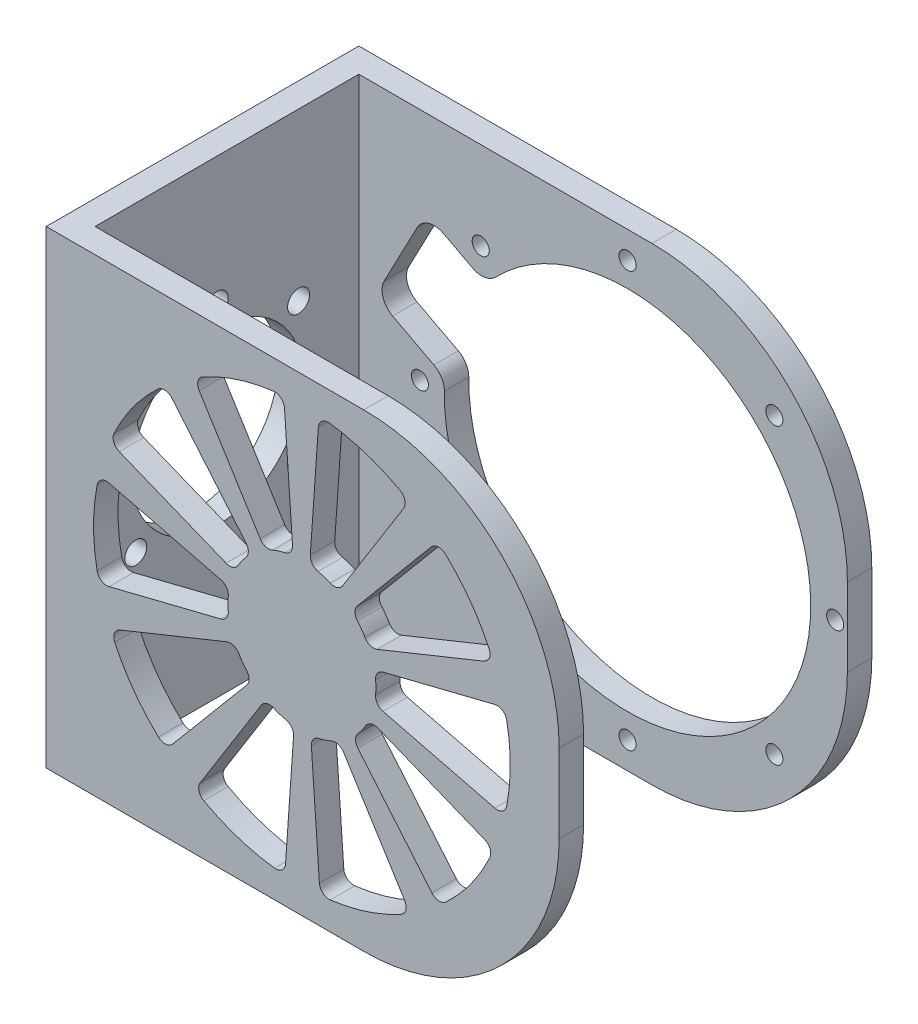
SolidWorks part; units mm, degrees
material "6061 合金"
ref_plane "前视基准面" through (0, 0, 0) normal (0, 0, 1) x (1, 0, 0)
ref_plane "上视基准面" through (0, 0, 0) normal (0, 1, 0) x (1, 0, 0)
ref_plane "右视基准面" through (0, 0, 0) normal (1, 0, 0) x (0, 0, -1)
other "Configuration Table"
sketch "草图1" plane through (0, 0, 0) normal (1, 0, 0) x (0, 0, -1)
  line L0 (-83.5786, 0) -> (71.0535, 0) construction
  line L1 (0, 49.275) -> (0, -51.1598) construction
  line L3 (-32, 48) -> (32, 48)
  line L4 (-32, 48) -> (-32, -48)
  line L5 (-32, -48) -> (32, -48)
  line L6 (32, 48) -> (32, -48)
  dimension "D1" = 64
  dimension "D2" = 96
extrude "凸台-拉伸1" add sketch "草图1" along normal blind 5
sketch "草图3" plane through (5, 0, 0) normal (1, 0, 0) x (0, 0, -1)
  line L0 (32, 48) -> (-32, 48) construction
  line L1 (27, 48) -> (32, 48)
  line L2 (27, 48) -> (27, -48)
  line L3 (27, -48) -> (32, -48)
  line L4 (32, 48) -> (32, -48)
  line L5 (0, 33.3664) -> (0, -30.3664) construction
  line L6 (-27, -48) -> (-32, -48)
  line L7 (-32, 48) -> (-32, -48)
  line L8 (-27, 48) -> (-32, 48)
  line L9 (-27, 48) -> (-27, -48)
  dimension "D1" = 5
extrude "凸台-拉伸2" add sketch "草图3" along normal blind 100 contours L2 L1 L4 L3
sketch "草图4" plane through (0, 0, 0) normal (-1, 0, 0) x (0, 0, 1)
  line L0 (-42.5996, 0) -> (43.5329, 0) construction
  line L1 (2, 63.7809) -> (2, -33.233) construction
  line L2 (32, 48) -> (32, -48) construction
  line L3 (2, 0) -> (18.6615, 13.9806) construction
  circle A0 centre (2, 0) radius 46 construction
  circle A1 centre (2, 0) radius 21.75 construction
  circle A2 centre (2, 21.75) radius 2.25
  circle A15 centre (18.6615, 13.9806) radius 2.25
  circle A16 centre (-14.6615, 13.9806) radius 2.25
  circle A17 centre (2, -21.75) radius 2.25
  circle A18 centre (18.6615, -13.9806) radius 2.25
  circle A19 centre (-14.6615, -13.9806) radius 2.25
  circle A20 centre (2, 0) radius 17.5
  point P24 (2, 0)
  point P28 (2, 0)
  dimension "D2" = 92
  dimension "D3" = 43.5
  dimension "D4" = 4.5
  dimension "D6" = 35
  dimension "D1" = 30
  dimension "D5" = 50
extrude "切除-拉伸1" cut sketch "草图4" against normal blind 100
sketch "草图5" plane through (0, 0, -32) normal (0, 0, -1) x (-1, 0, 0)
  line L0 (0, 0) -> (-122.5794, 0) construction
  line L1 (0, -48) -> (0, 48) construction
  circle A0 centre (-60, 0) radius 42.5 construction
  circle A1 centre (-60, 42.5) radius 1.75
  circle A2 centre (-29.948, 30.052) radius 1.75
  circle A3 centre (-17.5, 0) radius 1.75
  circle A4 centre (-29.948, -30.052) radius 1.75
  circle A5 centre (-60, -42.5) radius 1.75
  circle A6 centre (-90.052, -30.052) radius 1.75
  circle A7 centre (-102.5, 0) radius 1.75
  circle A8 centre (-90.052, 30.052) radius 1.75
  circle A9 centre (-60, 0) radius 37.5
  point P25 (-60, 0)
  dimension "D1" = 85
  dimension "D3" = 3.5
  dimension "D5" = 75
  dimension "D2" = 60
  dimension "D4" = 8
extrude "切除-拉伸2" cut sketch "草图5" against normal blind 22
fillet "圆角1" radius 40 4 edges at (105, -48, -29.5) (105, 48, -29.5) (2.5, 48, 32) (2.5, -48, 32)
sketch "草图6" plane through (0, 0, -27) normal (0, 0, 1) x (1, 0, 0)
  line L0 (10.2147, 13.9946) -> (16.9094, 26.7361)
  line L1 (22.3109, 28.4166) -> (38.876, 19.7129)
  line L2 (38.876, 19.7129) -> (28.4603, -0.1106)
  line L3 (28.4603, -0.1106) -> (11.8951, 8.5931)
  circle A0 centre (29.948, 30.052) radius 1.75 construction
  circle A1 centre (17.5, 0) radius 1.75 construction
  arc A2 (10.2147, 13.9946) -> (11.8951, 8.5931) centre (13.7556, 12.1341) ccw
  arc A3 (16.9094, 26.7361) -> (22.3109, 28.4166) centre (20.4503, 24.8756) cw
  dimension "D4" = 4
  dimension "D1" = 5
  dimension "D2" = 5
  dimension "D3" = 10
extrude "切除-拉伸3" cut sketch "草图6" against normal blind 10
fillet "圆角2" radius 4 2 edges at (22.617, 2.9596, -29.5) (31.0437, 23.8282, -29.5)
sketch "草图7" plane through (5, 0, 0) normal (1, 0, 0) x (0, 0, -1)
  line L1 (-27, 48) -> (8, 48)
  line L3 (-27, -48) -> (8, -48)
  line L5 (-27, 48) -> (0, 0) construction
  line L6 (-27, -48) -> (0, 0) construction
  line L7 (-27, 48) -> (-32, 48)
  line L9 (-27, -48) -> (-32, -48)
  line L10 (-32, 48) -> (-32, -48)
  arc A0 (-32, -8) -> (8, -48) centre (8, -8) ccw construction
  arc A1 (8, 48) -> (-32, 8) centre (8, 8) ccw construction
  arc A2 (-32, -8) -> (8, -48) centre (8, -8) ccw
  arc A3 (8, 48) -> (-32, 8) centre (8, 8) ccw
  point P0 (0, 0)
  arc M11 (8, 48) -> (-32, 8) centre (8, 8) ccw
  arc M13 (-32, -8) -> (8, -48) centre (8, -8) ccw
extrude "凸台-拉伸3" add sketch "草图7" against normal blind 5 contours L7 L10 L1 M11 | L10 L9 L3 M13
sketch "草图8" plane through (0, 0, 32) normal (0, 0, 1) x (1, 0, 0)
  line L4 (5, -48) -> (65, -48)
  line L5 (105, -8) -> (105, 8)
  line L6 (65, 48) -> (5, 48)
  line L7 (5, 48) -> (5, -48)
  line L8 (5, -48) -> (65, -48)
  line L9 (105, -8) -> (105, 8)
  line L10 (65, 48) -> (5, 48)
  line L11 (5, 48) -> (5, -48)
  arc A2 (65, -48) -> (105, -8) centre (65, -8) ccw
  arc A3 (105, 8) -> (65, 48) centre (65, 8) ccw
  arc A4 (65, -48) -> (105, -8) centre (65, -8) ccw
  arc A5 (105, 8) -> (65, 48) centre (65, 8) ccw
  dimension "D1" = 0
extrude "凸台-拉伸4" add sketch "草图8" against normal blind 5
sketch "草图9" plane through (0, 0, 32) normal (0, 0, 1) x (1, 0, 0)
  line L0 (0, 48) -> (0, -48) construction
  line L1 (0, 48) -> (65, 48) construction
  line L2 (68.9348, 3.4743) -> (91.8201, 9.1803)
  line L3 (68.9348, -3.4743) -> (91.8201, -9.1803)
  line L4 (55, 0) -> (95, 0) construction
  line L5 (67.8754, -6.9601) -> (89.7439, -15.7955)
  line L6 (63.791, -12.5817) -> (78.9518, -30.6496)
  line L7 (54.5597, -1.5802) -> (86.9204, -25.0916) construction
  line L8 (60.885, -14.779) -> (73.3837, -34.781)
  line L9 (54.2765, -16.9263) -> (55.9217, -40.4548)
  line L10 (53.2747, -2.5999) -> (65.6353, -40.6421) construction
  line L11 (50.6339, -16.9958) -> (48.9886, -40.5243)
  line L12 (44.0253, -14.8486) -> (31.5267, -34.8506)
  line L13 (51.6357, -2.6694) -> (39.275, -40.7117) construction
  line L14 (41.0376, -12.7638) -> (25.8768, -30.8317)
  line L15 (36.9532, -7.1422) -> (15.0847, -15.9777)
  line L16 (50.2689, -1.7624) -> (17.9082, -25.2738) construction
  line L17 (35.7615, -3.6995) -> (12.8761, -9.4054)
  line L18 (35.7615, 3.2492) -> (12.8761, 8.9552)
  line L19 (49.6963, -0.2251) -> (9.6963, -0.2251) construction
  line L20 (36.8209, 6.735) -> (14.9524, 15.5704)
  line L21 (40.9052, 12.3566) -> (25.7445, 30.4244)
  line L22 (50.1366, 1.3551) -> (17.7759, 24.8665) construction
  line L23 (43.8112, 14.5539) -> (31.3126, 34.5559)
  line L24 (50.4198, 16.7011) -> (48.7745, 40.2296)
  line L25 (51.4216, 2.3747) -> (39.0609, 40.417) construction
  line L26 (54.0623, 16.7707) -> (55.7076, 40.2992)
  line L27 (60.6709, 14.6235) -> (73.1696, 34.6255)
  line L28 (53.0605, 2.4443) -> (65.4212, 40.4866) construction
  line L29 (63.6587, 12.5387) -> (78.8194, 30.6066)
  line L30 (67.743, 6.9171) -> (89.6115, 15.7526)
  line L31 (54.4274, 1.5372) -> (86.7881, 25.0486) construction
  arc A0 (94.2673, -7.6207) -> (94.2673, 7.6207) centre (55, 0) ccw
  arc A1 (67.4299, -1.3222) -> (67.4299, 1.3222) centre (55, 0) ccw
  arc A2 (91.8201, -9.1803) -> (94.2673, -7.6207) centre (92.304, -7.2397) ccw
  arc A3 (91.8201, 9.1803) -> (94.2673, 7.6207) centre (92.304, 7.2397) cw
  arc A4 (67.4299, -1.3222) -> (68.9348, -3.4743) centre (69.4187, -1.5337) ccw
  arc A5 (67.4299, 1.3222) -> (68.9348, 3.4743) centre (69.4187, 1.5337) cw
  arc A6 (81.8483, -30.8263) -> (90.807, -18.4957) centre (54.5597, -1.5802) ccw
  arc A7 (63.8385, -9.956) -> (65.3929, -7.8166) centre (54.5597, -1.5802) ccw
  arc A8 (78.9518, -30.6496) -> (81.8483, -30.8263) centre (80.4839, -29.364) ccw
  arc A9 (89.7439, -15.7955) -> (90.807, -18.4957) centre (88.9946, -17.6499) cw
  arc A10 (63.8385, -9.956) -> (63.791, -12.5817) centre (65.3231, -11.2961) ccw
  arc A11 (65.3929, -7.8166) -> (67.8754, -6.9601) centre (67.1262, -8.8145) cw
  arc A12 (58.1612, -42.3003) -> (72.6567, -37.5904) centre (53.2747, -2.5999) ccw
  arc A13 (55.8582, -14.83) -> (58.3732, -14.0128) centre (53.2747, -2.5999) ccw
  arc A14 (55.9217, -40.4548) -> (58.1612, -42.3003) centre (57.9169, -40.3152) ccw
  arc A15 (73.3837, -34.781) -> (72.6567, -37.5904) centre (71.6876, -35.8409) cw
  arc A16 (55.8582, -14.83) -> (54.2765, -16.9263) centre (56.2716, -16.7868) ccw
  arc A17 (58.3732, -14.0128) -> (60.885, -14.779) centre (59.1889, -15.8389) cw
  arc A18 (32.2537, -37.66) -> (46.7492, -42.3698) centre (51.6357, -2.6694) ccw
  arc A19 (46.5372, -14.0824) -> (49.0522, -14.8995) centre (51.6357, -2.6694) ccw
  arc A20 (31.5267, -34.8506) -> (32.2537, -37.66) centre (33.2228, -35.9104) ccw
  arc A21 (48.9886, -40.5243) -> (46.7492, -42.3698) centre (46.9935, -40.3848) cw
  arc A22 (46.5372, -14.0824) -> (44.0253, -14.8486) centre (45.7214, -15.9084) ccw
  arc A23 (49.0522, -14.8995) -> (50.6339, -16.9958) centre (48.6388, -16.8563) cw
  arc A24 (14.0216, -18.6778) -> (22.9803, -31.0084) centre (50.2689, -1.7624) ccw
  arc A25 (39.4357, -7.9988) -> (40.9901, -10.1381) centre (50.2689, -1.7624) ccw
  arc A26 (15.0847, -15.9777) -> (14.0216, -18.6778) centre (15.8339, -17.8321) ccw
  arc A27 (25.8768, -30.8317) -> (22.9803, -31.0084) centre (24.3447, -29.5461) cw
  arc A28 (39.4357, -7.9988) -> (36.9532, -7.1422) centre (37.7024, -8.9966) ccw
  arc A29 (40.9901, -10.1381) -> (41.0376, -12.7638) centre (39.5055, -11.4783) cw
  arc A30 (10.4289, 7.3956) -> (10.4289, -7.8459) centre (49.6963, -0.2251) ccw
  arc A31 (37.2664, 1.0971) -> (37.2664, -1.5473) centre (49.6963, -0.2251) ccw
  arc A32 (12.8761, 8.9552) -> (10.4289, 7.3956) centre (12.3923, 7.0146) ccw
  arc A33 (12.8761, -9.4054) -> (10.4289, -7.8459) centre (12.3923, -7.4648) cw
  arc A34 (37.2664, 1.0971) -> (35.7615, 3.2492) centre (35.2776, 1.3086) ccw
  arc A35 (37.2664, -1.5473) -> (35.7615, -3.6995) centre (35.2776, -1.7589) cw
  arc A36 (22.848, 30.6012) -> (13.8893, 18.2706) centre (50.1366, 1.3551) ccw
  arc A37 (40.8577, 9.7309) -> (39.3034, 7.5915) centre (50.1366, 1.3551) ccw
  arc A38 (25.7445, 30.4244) -> (22.848, 30.6012) centre (24.2124, 29.1389) ccw
  arc A39 (14.9524, 15.5704) -> (13.8893, 18.2706) centre (15.7016, 17.4248) cw
  arc A40 (40.8577, 9.7309) -> (40.9052, 12.3566) centre (39.3731, 11.071) ccw
  arc A41 (39.3034, 7.5915) -> (36.8209, 6.735) centre (37.5701, 8.5893) cw
  arc A42 (46.5351, 42.0751) -> (32.0396, 37.3653) centre (51.4216, 2.3747) ccw
  arc A43 (48.838, 14.6048) -> (46.3231, 13.7877) centre (51.4216, 2.3747) ccw
  arc A44 (48.7745, 40.2296) -> (46.5351, 42.0751) centre (46.7794, 40.0901) ccw
  arc A45 (31.3126, 34.5559) -> (32.0396, 37.3653) centre (33.0087, 35.6157) cw
  arc A46 (48.838, 14.6048) -> (50.4198, 16.7011) centre (48.4247, 16.5616) ccw
  arc A47 (46.3231, 13.7877) -> (43.8112, 14.5539) centre (45.5073, 15.6137) cw
  arc A48 (72.4426, 37.4348) -> (57.9471, 42.1447) centre (53.0605, 2.4443) ccw
  arc A49 (58.1591, 13.8572) -> (55.6441, 14.6744) centre (53.0605, 2.4443) ccw
  arc A50 (73.1696, 34.6255) -> (72.4426, 37.4348) centre (71.4735, 35.6853) ccw
  arc A51 (55.7076, 40.2992) -> (57.9471, 42.1447) centre (57.7027, 40.1597) cw
  arc A52 (58.1591, 13.8572) -> (60.6709, 14.6235) centre (58.9748, 15.6833) ccw
  arc A53 (55.6441, 14.6744) -> (54.0623, 16.7707) centre (56.0575, 16.6312) cw
  arc A54 (90.6747, 18.4527) -> (81.716, 30.7833) centre (54.4274, 1.5372) ccw
  arc A55 (65.2605, 7.7736) -> (63.7062, 9.913) centre (54.4274, 1.5372) ccw
  arc A56 (89.6115, 15.7526) -> (90.6747, 18.4527) centre (88.8623, 17.6069) ccw
  arc A57 (78.8194, 30.6066) -> (81.716, 30.7833) centre (80.3515, 29.321) cw
  arc A58 (65.2605, 7.7736) -> (67.743, 6.9171) centre (66.9938, 8.7715) ccw
  arc A59 (63.7062, 9.913) -> (63.6587, 12.5387) centre (65.1908, 11.2531) cw
  point P18 (-38.3142, -38.7462)
  point P19 (34.4989, -14.4238)
  point P146 (52.3481, -0.2251)
  point P174 (52.3481, -0.1126)
  point P175 (51.0172, 0)
  point P176 (50.4209, 0)
  dimension "D1" = 55
  dimension "D2" = 80
  dimension "D3" = 48
  dimension "D4" = 25
  dimension "D7" = 2
  dimension "D5" = 14
  dimension "D6" = 14
  dimension "D8" = 10
extrude "切除-拉伸4" cut sketch "草图9" against normal blind 5
